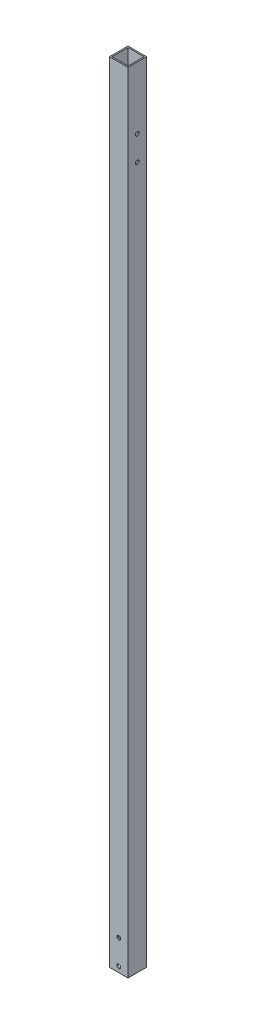
SolidWorks part; units mm, degrees
ref_plane "前视基准面" through (0, 0, 0) normal (0, 0, 1) x (1, 0, 0)
ref_plane "上视基准面" through (0, 0, 0) normal (0, 1, 0) x (1, 0, 0)
ref_plane "右视基准面" through (0, 0, 0) normal (1, 0, 0) x (0, 0, -1)
sketch "草图1" plane through (0, 0, 0) normal (0, 1, 0) x (1, 0, 0)
  line L1 (-7.5, -7.5) -> (7.5, -7.5)
  line L2 (-7.5, -7.5) -> (-7.5, 7.5)
  line L3 (-7.5, 7.5) -> (7.5, 7.5)
  line L4 (7.5, -7.5) -> (7.5, 7.5)
  line L5 (-7.5, -7.5) -> (7.5, 7.5) construction
  line L6 (-7.5, 7.5) -> (7.5, -7.5) construction
  point P0 (0, 0)
  dimension "D1" = 15
  dimension "D2" = 15
extrude "拉伸-薄壁1" add sketch "草图1" along normal blind 640 thin thin type one direction reverse wall 1
sketch "草图2" plane through (0, 0, 7.5) normal (0, 0, 1) x (1, 0, 0)
  line L0 (0, 0) -> (0, 640) construction
  line L1 (-7.5, 640) -> (7.5, 640) construction
  line L2 (-7.5, 0) -> (7.5, 0) construction
  circle A0 centre (0, 4.5) radius 1.6
  circle A1 centre (0, 24.5) radius 1.6
  dimension "D1" = 3.2
  dimension "D2" = 4.5
  dimension "D3" = 20
extrude "切除-拉伸1" cut sketch "草图2" against normal through all
sketch "草图3" plane through (7.5, 0, 0) normal (1, 0, 0) x (0, 0, -1)
  line L0 (0, 0) -> (0, 640) construction
  line L1 (-7.5, 640) -> (7.5, 640) construction
  line L2 (-7.5, 0) -> (7.5, 0) construction
  circle A0 centre (0, 589.5) radius 1.6
  circle A1 centre (0, 569.5) radius 1.6
  dimension "D1" = 3.2
  dimension "D3" = 20
  dimension "D2" = 589.5
extrude "切除-拉伸2" cut sketch "草图3" against normal through all
